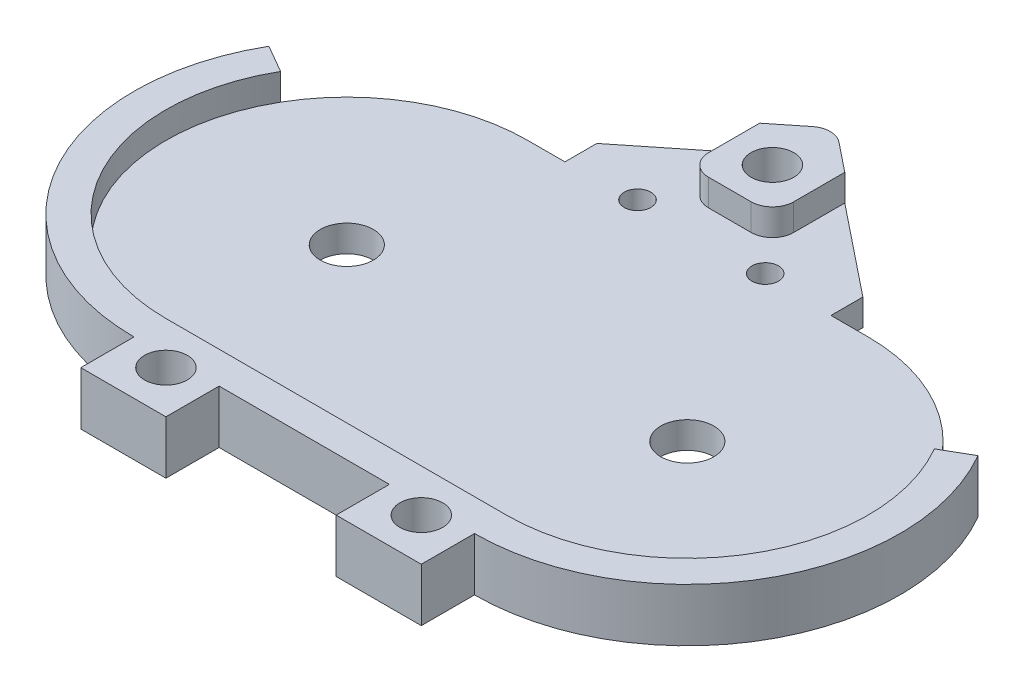
SolidWorks part; units mm, degrees
material "PLA"
ref_plane "Front Plane" through (0, 0, 0) normal (0, 0, 1) x (1, 0, 0)
ref_plane "Top Plane" through (0, 0, 0) normal (0, 1, 0) x (1, 0, 0)
ref_plane "Right Plane" through (0, 0, 0) normal (1, 0, 0) x (0, 0, -1)
sketch "Sketch1" plane through (0, 0, 0) normal (0, 1, 0) x (1, 0, 0)
  line L0 (-40.64, 0) -> (40.64, 0) construction
  line L1 (0, 34.29) -> (0, -31.75) construction
  line L2 (20.32, 0) -> (7.62, 21.997) construction
  line L3 (-20.32, 0) -> (-7.62, 21.997) construction
  line L11 (-20.32, 25.4) -> (-15.875, 25.4)
  line L16 (20.32, 25.4) -> (15.875, 25.4)
  line L17 (-20.32, -25.4) -> (-20.32, -31.75)
  line L18 (-20.32, -31.75) -> (20.32, -31.75)
  line L19 (20.32, -31.75) -> (20.32, -25.4)
  line L22 (-15.875, 25.4) -> (0, 38.1)
  line L23 (0, 38.1) -> (15.875, 25.4)
  circle A3 centre (20.32, 0) radius 3.175
  circle A4 centre (7.62, 21.997) radius 1.5875
  circle A5 centre (-20.32, 0) radius 3.175
  circle A6 centre (-7.62, 21.997) radius 1.5875
  arc A10 (-20.32, 25.4) -> (-20.32, -25.4) centre (-20.32, 0) ccw
  arc A11 (20.32, 25.4) -> (20.32, -25.4) centre (20.32, 0) cw
  dimension "D1" = 25.4
  dimension "D4" = 6.35
  dimension "D5" = 3.175
  dimension "D6" = 25.4
  dimension "D2" = 60
  dimension "D3" = 20.32
  dimension "D7" = 12.7
  dimension "D8" = 31.75
  dimension "D9" = 6.35
extrude "Boss-Extrude1" add sketch "Sketch1" along normal blind 3.175
sketch "Sketch4" [suppressed] plane through (0, 3.175, 0) normal (0, 1, 0) x (1, 0, 0)
  line L1 (-20.32, -25.4) -> (-20.32, -31.75) construction
  line L2 (-20.32, -31.75) -> (20.32, -31.75) construction
  line L3 (20.32, -31.75) -> (20.32, -25.4) construction
  point P0 (-7.62, 21.997)
  point P1 (0, 21.997)
  point P2 (20.32, 0)
  point P4 (7.62, -25.4)
  point P8 (7.62, 21.997)
  point P9 (-20.32, 0)
  point P10 (-7.62, -25.4)
  dimension "D1" = 12.7
  dimension "D2" = 6.35
  dimension "D3" = 12.7
  dimension "D4" = 7.62
hole_wizard "#10 (0.1935) Diameter Hole1" [suppressed] positions "Sketch5" profile "Sketch6" hole size "#10" standard "ANSI Inch"
sketch "Sketch5" [suppressed] plane through (0, 3.175, 0) normal (0, 1, 0) x (1, 0, 0)
  point P6 (0, 21.997)
  point P9 (0, 21.997)
  point P11 (-7.62, -25.4)
  point P14 (7.62, -25.4)
sketch "Sketch6" plane through (0, 3.175, -21.997) normal (1, 0, 0) x (0, 0, 1)
  line L0 (0, 0) -> (0, 3.175)
  line L1 (0, 3.175) -> (2.4574, 3.175)
  line L2 (2.4574, 3.175) -> (2.4574, 0)
  line L5 (2.4574, 0) -> (0, 0)
  line L11 (0, -6.35) -> (0, 107.95) construction
  dimension "Thru Hole Dia." = 4.9149
  dimension "Thru Hole Depth" = 3.175
sketch "Sketch7" plane through (0, 3.175, 0) normal (0, 1, 0) x (1, 0, 0)
  line L0 (0, 0) -> (0, 33.9313) construction
  line L1 (-20.32, 0) -> (-42.317, 12.7)
  line L2 (0, 0) -> (-20.32, 0) construction
  line L3 (-15.875, 25.4) -> (-20.32, 25.4)
  line L4 (-20.32, 21.59) -> (-15.875, 21.59)
  line L5 (-15.875, 21.59) -> (-15.875, 25.4)
  circle A0 centre (-20.32, 0) radius 25.4
  arc A1 (-20.32, 25.4) -> (-20.32, -25.4) centre (-20.32, 0) ccw construction
  circle A2 centre (-20.32, 0) radius 21.59
  line M9 (-15.875, 25.4) -> (-20.32, 25.4)
  arc M10 (-20.32, 25.4) -> (-20.32, -25.4) centre (-20.32, 0) ccw
  dimension "D1" = 43.18
  dimension "D2" = 150
extrude "Cut-Extrude1" cut sketch "Sketch7" against normal up to next contours A2 L4 L5 A0 L1 M10 | A0 L5 M9
sketch "Sketch9" plane through (0, 3.175, 0) normal (0, 1, 0) x (1, 0, 0)
  line L0 (-39.0175, 10.795) -> (-42.317, 12.7)
  line L1 (0, 38.1) -> (-5.08, 34.036)
  line L2 (-20.32, -25.4) -> (-20.32, -31.75)
  line L3 (-20.32, -31.75) -> (-10.16, -31.75)
  line L5 (-20.32, -21.59) -> (0, -21.59)
  line L6 (0, -21.59) -> (0, -25.4)
  line L12 (0, 25.4) -> (-5.08, 25.4)
  line L13 (-5.08, 25.4) -> (-5.08, 34.036)
  line L14 (0, 25.4) -> (0, 38.1)
  line L15 (0, -25.4) -> (-10.16, -25.4)
  line L16 (-10.16, -25.4) -> (-10.16, -31.75)
  line L17 (-15.875, 25.4) -> (0, 38.1) construction
  arc A0 (-42.317, 12.7) -> (-20.32, -25.4) centre (-20.32, 0) ccw
  arc A1 (-39.0175, 10.795) -> (-20.32, -21.59) centre (-20.32, 0) ccw
  arc A2 (-42.317, 12.7) -> (-20.32, -25.4) centre (-20.32, 0) ccw construction
  arc A3 (-20.32, 21.59) -> (-39.0175, 10.795) centre (-20.32, 0) ccw construction
  dimension "D1" = 5.08
  dimension "D2" = 57.15
  dimension "D3" = 10.16
extrude "Boss-Extrude2" add sketch "Sketch9" along normal blind 3.175
mirror "Mirror1" about plane through (0, 0, 0) normal (1, 0, 0) of "Boss-Extrude2", "Cut-Extrude1"
sketch "Sketch13" plane through (0, 6.35, 0) normal (0, 1, 0) x (1, 0, 0)
  line L0 (0, 0) -> (0, -5.6853) construction
  line L2 (5.08, 25.4) -> (-5.08, 25.4) construction
  line L3 (-20.32, -31.75) -> (-10.16, -31.75) construction
  point P0 (0, 30.48)
  point P1 (-15.24, -26.67)
  point P10 (15.24, -26.67)
  dimension "D1" = 15.24
  dimension "D2" = 5.08
  dimension "D3" = 5.08
hole_wizard "Tap Drill for #10 Helicoil2" positions "Sketch14" profile "Sketch15" hole size "#10-32" standard "ANSI Inch" end condition up to next
sketch "Sketch14" plane through (0, 6.35, 0) normal (0, 1, 0) x (1, 0, 0)
  point P0 (-15.24, -26.67)
  point P3 (15.24, -26.67)
  point P6 (0, 30.48)
sketch "Sketch15" plane through (-15.24, 6.35, 26.67) normal (1, 0, 0) x (0, 0, 1)
  line L0 (0, 0) -> (0, 6.35)
  line L1 (0, 6.35) -> (2.5527, 6.35)
  line L2 (2.5527, 6.35) -> (2.5527, 0)
  line L5 (2.5527, 0) -> (0, 0)
  line L11 (0, -6.35) -> (0, 107.95) construction
  dimension "Thru Hole Dia." = 5.1054
  dimension "Thru Hole Depth" = 6.35
fillet "Fillet1" radius 2.54 3 edges at (0, 3.175, -38.1) (5.08, 4.7625, -25.4) (-5.08, 4.7625, -25.4)
sketch "Sketch16" plane through (0, 3.175, 0) normal (0, 1, 0) x (1, 0, 0)
  line L0 (-39.0175, 10.795) -> (-50.016, 17.145)
  line L1 (-50.016, 17.145) -> (-55.096, 8.3462)
  line L2 (-55.096, 8.3462) -> (-44.0975, 1.9962)
  line L3 (-44.0975, 1.9962) -> (-39.0175, 10.795)
  line L4 (-39.0175, 10.795) -> (-42.317, 12.7) construction
  line L5 (0, 0) -> (0, -14.9889) construction
  line L6 (10.16, -25.4) -> (-10.16, -25.4) construction
  line L7 (5.08, -35.56) -> (-5.08, -35.56)
  line L9 (5.08, -25.4) -> (-5.08, -25.4)
  line L11 (5.08, -35.56) -> (-5.08, -25.4) construction
  line L12 (5.08, -25.4) -> (-5.08, -35.56) construction
  line L13 (-5.08, -35.56) -> (-10.16, -31.75)
  line L14 (-10.16, -31.75) -> (-5.08, -25.4)
  line L15 (5.08, -35.56) -> (10.16, -31.75)
  line L16 (10.16, -31.75) -> (5.08, -25.4)
  line L17 (44.0975, 1.9962) -> (39.0175, 10.795)
  line L18 (55.096, 8.3462) -> (44.0975, 1.9962)
  line L19 (50.016, 17.145) -> (55.096, 8.3462)
  line L20 (39.0175, 10.795) -> (50.016, 17.145)
  point P9 (0, -30.48)
  point P18 (0, -25.4)
  dimension "D1" = 10.16
  dimension "D2" = 12.7
  dimension "D3" = 10.16
  dimension "D4" = 10.16
extrude "Boss-Extrude3" [suppressed] add sketch "Sketch16" against normal up to surface (3.175 mm away)
fillet "Fillet2" [suppressed] radius 6.35
sketch "Sketch17" [suppressed] plane through (0, 3.175, 0) normal (0, 1, 0) x (1, 0, 0)
  line L0 (-50.016, 17.145) -> (-55.096, 8.3462) construction
  line L1 (-42.317, 12.7) -> (-50.016, 17.145) construction
  line L2 (-2.9633, -35.56) -> (2.9633, -35.56) construction
  line L3 (0, 0) -> (0, -30.48) construction
  point P0 (-48.1566, 10.2056)
  point P1 (0, -30.48)
  point P11 (48.1566, 10.2056)
  dimension "D1" = 5.08
  dimension "D2" = 5.08
  dimension "D3" = 5.08
hole_wizard "Tap Drill for #10 Helicoil3" [suppressed] positions "Sketch18" profile "Sketch19" hole size "#10-32" standard "ANSI Inch"
sketch "Sketch18" [suppressed] plane through (0, 3.175, 0) normal (0, 1, 0) x (1, 0, 0)
  point P0 (-48.1566, 10.2056)
  point P3 (0, -30.48)
  point P6 (48.1566, 10.2056)
sketch "Sketch19" plane through (-48.1566, 3.175, -10.2056) normal (1, 0, 0) x (0, 0, 1)
  line L0 (0, 0) -> (0, 3.175)
  line L1 (0, 3.175) -> (2.5527, 3.175)
  line L2 (2.5527, 3.175) -> (2.5527, 0)
  line L5 (2.5527, 0) -> (0, 0)
  line L11 (0, -6.35) -> (0, 107.95) construction
  dimension "Thru Hole Dia." = 5.1054
  dimension "Thru Hole Depth" = 3.175
sketch "Sketch20" plane through (0, 3.175, 0) normal (0, 1, 0) x (1, 0, 0)
  line L1 (-10.16, -31.75) -> (10.16, -31.75)
  line L2 (-10.16, -31.75) -> (-10.16, -25.4)
  line L3 (-10.16, -25.4) -> (10.16, -25.4)
  line L4 (10.16, -31.75) -> (10.16, -25.4)
extrude "Cut-Extrude2" cut sketch "Sketch20" against normal up to next
